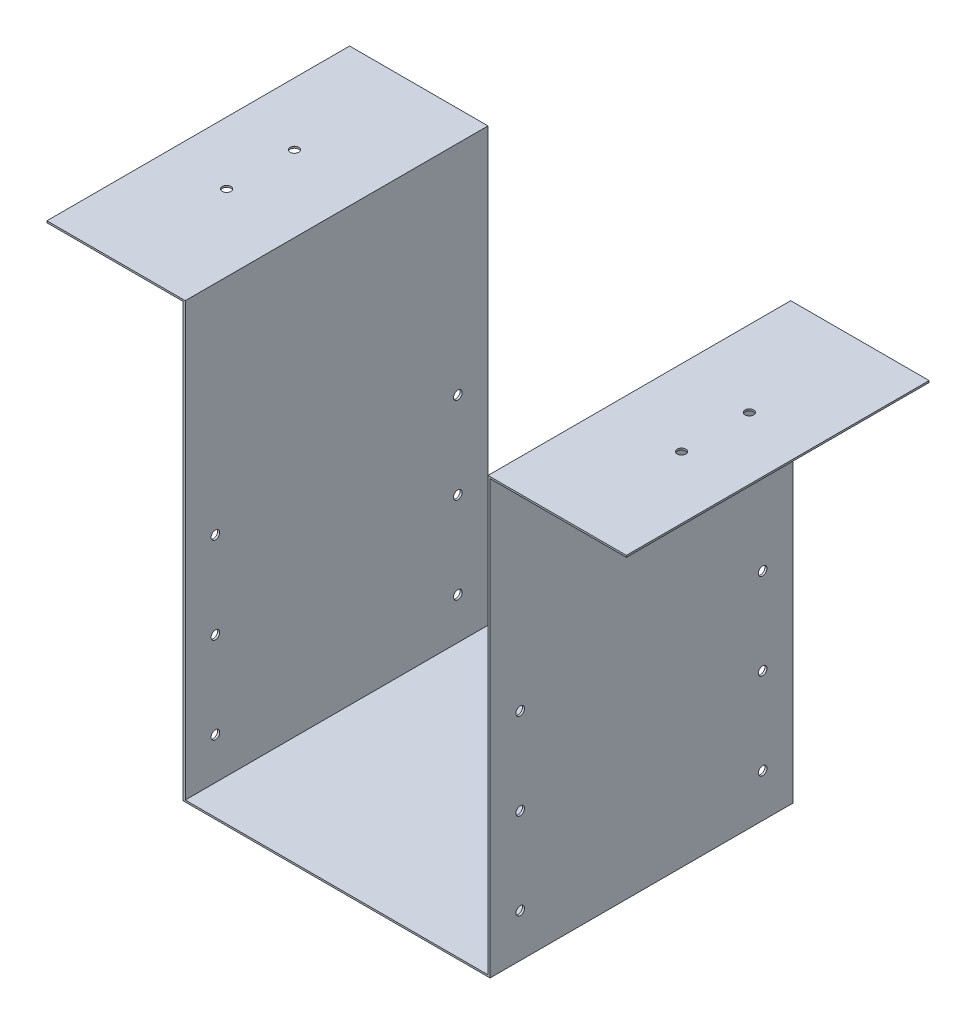
SolidWorks part; units mm, degrees
ref_plane "Front Plane" through (0, 0, 0) normal (0, 0, 1) x (1, 0, 0)
ref_plane "Top Plane" through (0, 0, 0) normal (0, 1, 0) x (1, 0, 0)
ref_plane "Right Plane" through (0, 0, 0) normal (1, 0, 0) x (0, 0, -1)
sketch "Sketch1" plane through (0, 0, 0) normal (0, 1, 0) x (1, 0, 0)
  line L1 (-87.5, -87.5) -> (87.5, -87.5)
  line L2 (-87.5, -87.5) -> (-87.5, 87.5)
  line L3 (-87.5, 87.5) -> (87.5, 87.5)
  line L4 (87.5, -87.5) -> (87.5, 87.5)
  line L5 (-87.5, -87.5) -> (87.5, 87.5) construction
  line L6 (-87.5, 87.5) -> (87.5, -87.5) construction
  point P0 (0, 0)
  dimension "D1" = 175
extrude "Boss-Extrude1" add sketch "Sketch1" along normal blind 1
sketch "Sketch2" plane through (0, 0, 0) normal (0, -1, 0) x (1, 0, 0)
  line L0 (0, -87.5) -> (0, 87.5) construction
  line L1 (-87.5, -87.5) -> (-88.7, -87.5)
  line L2 (-87.5, -87.5) -> (-87.5, 87.5)
  line L3 (-87.5, 87.5) -> (-88.7, 87.5)
  line L4 (-88.7, -87.5) -> (-88.7, 87.5)
  line L5 (87.5, -87.5) -> (-87.5, -87.5) construction
  line L6 (-87.5, 87.5) -> (87.5, 87.5) construction
  line L7 (88.7, -87.5) -> (88.7, 87.5)
  line L8 (87.5, 87.5) -> (88.7, 87.5)
  line L9 (87.5, -87.5) -> (87.5, 87.5)
  line L10 (87.5, -87.5) -> (88.7, -87.5)
  dimension "D1" = 1.2
extrude "Boss-Extrude2" add sketch "Sketch2" against normal blind 250
sketch "Sketch3" plane through (0, 250, 0) normal (0, 1, 0) x (1, 0, 0)
  line L0 (0, 87.5) -> (0, -87.5) construction
  line L1 (-87.5, 87.5) -> (-167.5, 87.5)
  line L2 (-87.5, 87.5) -> (-87.5, -87.5)
  line L3 (-87.5, -87.5) -> (-167.5, -87.5)
  line L4 (-167.5, 87.5) -> (-167.5, -87.5)
  line L5 (87.5, 87.5) -> (-87.5, 87.5) construction
  line L6 (-87.5, -87.5) -> (87.5, -87.5) construction
  line L7 (167.5, 87.5) -> (167.5, -87.5)
  line L8 (87.5, -87.5) -> (167.5, -87.5)
  line L9 (87.5, 87.5) -> (87.5, -87.5)
  line L10 (87.5, 87.5) -> (167.5, 87.5)
  dimension "D1" = 80
extrude "Boss-Extrude3" add sketch "Sketch3" along normal blind 1
sketch "Sketch4" plane through (0, 251, 0) normal (0, 1, 0) x (1, 0, 0)
  line L0 (87.5, 0) -> (131.5, 0) construction
  line L1 (87.5, 0) -> (167.5, 0) construction
  line L2 (131.5, 0) -> (131.5, 19.6) construction
  line L3 (0, 87.5) -> (0, -87.5) construction
  line L4 (87.5, 87.5) -> (-87.5, 87.5) construction
  line L5 (-87.5, -87.5) -> (87.5, -87.5) construction
  line L6 (-131.5, 0) -> (-131.5, 19.6) construction
  line L7 (-87.5, 0) -> (-131.5, 0) construction
  circle A1 centre (131.5, 19.6) radius 2.5
  circle A2 centre (131.5, -19.6) radius 2.5
  circle A3 centre (-131.5, -19.6) radius 2.5
  circle A4 centre (-131.5, 19.6) radius 2.5
  dimension "D3" = 5
  dimension "D1" = 44
  dimension "D2" = 19.6
extrude "Cut-Extrude1" cut sketch "Sketch4" against normal blind 10
sketch "Sketch5" plane through (-88.7, 0, 0) normal (-1, 0, 0) x (0, 0, 1)
  line L0 (-87.5, 207.5) -> (87.5, 207.5) construction
  line L1 (-87.5, 250) -> (-87.5, 0) construction
  line L2 (87.5, 250) -> (87.5, 0) construction
  line L3 (-87.5, 177.5) -> (87.5, 177.5) construction
  line L4 (87.5, 250) -> (-87.5, 250) construction
  dimension "D1" = 42.5
  dimension "D2" = 30
sketch "Sketch6" plane through (88.7, 0, 0) normal (1, 0, 0) x (0, 0, -1)
  line L0 (87.5, 25) -> (70.0773, 25) construction
  line L1 (87.5, 250) -> (87.5, 0) construction
  line L2 (87.5, 0) -> (-87.5, 0) construction
  line L3 (0, 0) -> (0, 150.606) construction
  circle A0 centre (70.0773, 25) radius 2.5
  circle A1 centre (70.0773, 75) radius 2.5
  circle A2 centre (70.0773, 125) radius 2.5
  circle A3 centre (-70.0773, 125) radius 2.5
  circle A4 centre (-70.0773, 75) radius 2.5
  circle A5 centre (-70.0773, 25) radius 2.5
  dimension "D2" = 5
  dimension "D1" = 25
  dimension "D3" = 3
extrude "Cut-Extrude2" cut sketch "Sketch6" against normal blind 300
